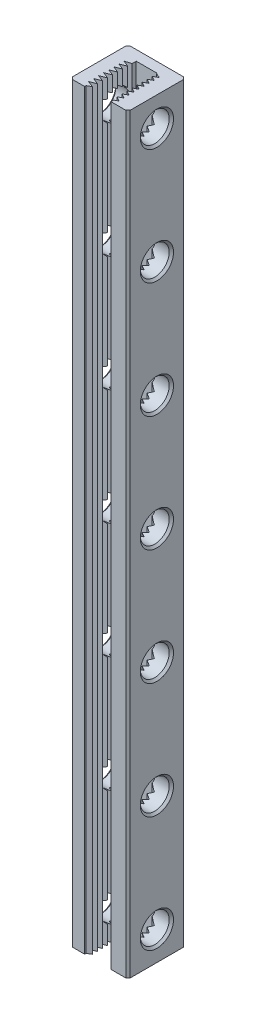
SolidWorks part; units mm, degrees
ref_plane "Front Plane" through (0, 0, 0) normal (0, 0, 1) x (1, 0, 0)
ref_plane "Top Plane" through (0, 0, 0) normal (0, 1, 0) x (1, 0, 0)
ref_plane "Right Plane" through (0, 0, 0) normal (1, 0, 0) x (0, 0, -1)
sketch "Sketch1" plane through (0, 0, 0) normal (0, 1, 0) x (1, 0, 0)
  line L1 (0, 0) -> (8, 0)
  line L2 (0, 0) -> (0, 8)
  line L3 (0, 8) -> (8, 8)
  line L4 (8, 0) -> (8, 8)
  dimension "D1" = 8
  dimension "D2" = 8
extrude "Boss-Extrude1" add sketch "Sketch1" along normal blind 300
sketch "Sketch2" plane through (0, 0, 0) normal (0, -1, 0) x (1, 0, 0)
  line L0 (5.652, 0) -> (2.0084, 0)
  line L1 (2.0084, 0) -> (2.0084, -0.2082)
  line L2 (2.0084, -0.2082) -> (2.54, -0.5151)
  line L3 (2.54, -0.5151) -> (1.6737, -0.8651)
  line L4 (1.6737, -0.8651) -> (2.54, -1.2151)
  line L5 (2.54, -1.2151) -> (1.6737, -1.5727)
  line L6 (1.6737, -1.5727) -> (2.54, -1.9151)
  line L7 (2.54, -1.9151) -> (1.6737, -2.2651)
  line L8 (1.6737, -2.2651) -> (2.54, -2.6151)
  line L9 (2.54, -2.6151) -> (1.6737, -2.9651)
  line L10 (1.6737, -2.9651) -> (2.54, -3.3151)
  line L11 (2.54, -3.3151) -> (1.6737, -3.6651)
  line L12 (1.6737, -3.6651) -> (2.54, -4.0151)
  line L13 (2.54, -4.0151) -> (1.6737, -4.3651)
  line L14 (1.6737, -4.3651) -> (2.54, -4.7151)
  line L15 (2.54, -4.7151) -> (1.6737, -5.0651)
  line L16 (1.6737, -5.0651) -> (2.54, -5.4151)
  line L17 (2.54, -5.4151) -> (1.6737, -5.7651)
  line L18 (1.6737, -5.7651) -> (2.54, -6.0264)
  line L19 (2.54, -6.0264) -> (2.54, -6.6)
  line L20 (2.54, -6.6) -> (5.46, -6.6)
  line L21 (5.46, -6.6) -> (5.46, -6.4988)
  line L22 (5.46, -6.4988) -> (6.1067, -6.2375)
  line L23 (6.1067, -6.2375) -> (5.46, -5.8875)
  line L24 (5.46, -5.8875) -> (6.1067, -5.5375)
  line L25 (6.1067, -5.5375) -> (5.46, -5.1875)
  line L26 (5.46, -5.1875) -> (6.1067, -4.8375)
  line L27 (6.1067, -4.8375) -> (5.46, -4.4875)
  line L28 (5.46, -4.4875) -> (6.1067, -4.1375)
  line L29 (6.1067, -4.1375) -> (5.46, -3.7875)
  line L30 (5.46, -3.7875) -> (6.1067, -3.4375)
  line L31 (6.1067, -3.4375) -> (5.46, -3.0875)
  line L32 (5.46, -3.0875) -> (6.1067, -2.7375)
  line L33 (6.1067, -2.7375) -> (5.46, -2.3875)
  line L34 (5.46, -2.3875) -> (6.1067, -2.0375)
  line L35 (6.1067, -2.0375) -> (5.46, -1.6875)
  line L36 (5.46, -1.6875) -> (6.1067, -1.3451)
  line L37 (6.1067, -1.3451) -> (5.46, -0.9875)
  line L38 (5.46, -0.9875) -> (6.1067, -0.6375)
  line L39 (6.1067, -0.6375) -> (5.652, -0.375)
  line L40 (5.652, -0.375) -> (5.652, 0)
  line L41 (0, -8) -> (0, 0) construction
  line L42 (8, -8) -> (0, -8) construction
  line L43 (0, 0) -> (8, 0) construction
  point P41 (0, 0)
  point P42 (0, 0)
  point P43 (0, 0)
  point P44 (0, 0)
  point P51 (0, 0)
  point P52 (0, 0)
  point P53 (4, -6.6)
  dimension "D1" = 2.92
  dimension "D2" = 0.8663
  dimension "D3" = 6.6
  dimension "D4" = 0.6467
  dimension "D5" = 4.433
  dimension "D6" = 4
extrude "Cut-Extrude1" cut sketch "Sketch2" against normal through all contours L0 L1 L2 L3 L4 L5 L6 L7 L8 L9 L10 L11 L12 L13 L14 L15 L16 L17 L18 L19 L20 L21 L22 L23 L24 L25 L26 L27 L28 L29 L30 L31 L32 L33 L34 L35 L36 L37 L38 L39 L40
sketch "Sketch3" plane through (8, 0, 0) normal (1, 0, 0) x (0, 0, -1)
  line L0 (0, 0) -> (8, 0) construction
  line L1 (8, 300) -> (8, 0) construction
  circle A0 centre (4, 4) radius 2
  dimension "D1" = 4
  dimension "D2" = 4
  dimension "D3" = 4
extrude "Cut-Extrude2" cut sketch "Sketch3" against normal through all
chamfer "Chamfer1" distance 0.3 angle 45 2 edges at (0, 4, -6) (8, 4, -6)
chamfer "Chamfer2" distance 0.3 angle 45 4 edges at (0, 150, -8) (0, 150, 0) (8, 150, -8) (8, 150, 0)
pattern_linear "LPattern1" count 19 spacing 16 along (0, 1, 0) of "Cut-Extrude2", "Chamfer1"
sketch "Sketch4" plane through (8, 0, 0) normal (1, 0, 0) x (0, 0, -1)
  line L0 (0.3, 300) -> (7.7, 300) construction
  line L1 (8, 300) -> (0, 300)
  line L2 (8, 300) -> (8, 104)
  line L3 (8, 104) -> (0, 104)
  line L4 (0, 300) -> (0, 104)
  line L5 (0, 0) -> (0, 300) construction
  line L6 (8, 300) -> (8, 0) construction
  line L7 (0.3, 0) -> (7.7, 0) construction
  point P7 (0, 0)
  dimension "D1" = 104
extrude "Cut-Extrude3" cut sketch "Sketch4" against normal through all
